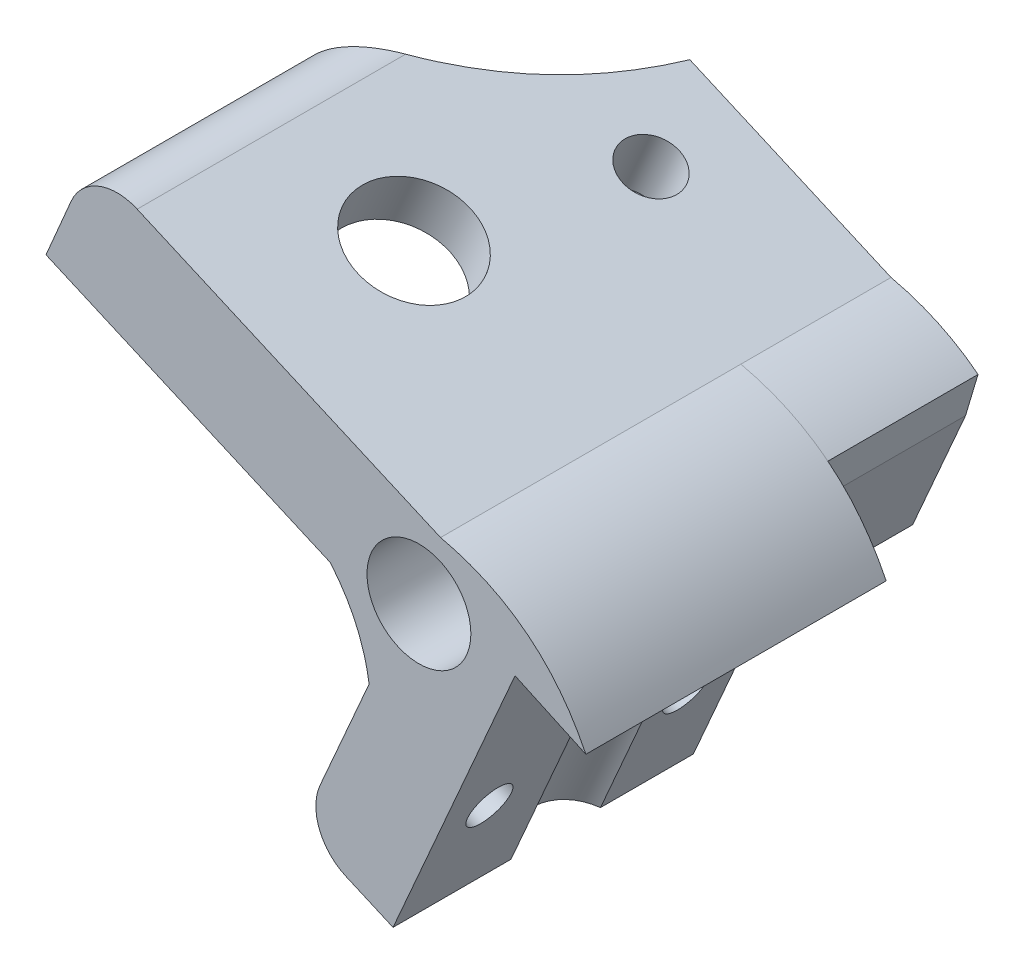
SolidWorks part; units mm, degrees
ref_plane "Front Plane" through (0, 0, 0) normal (0, 0, 1) x (1, 0, 0)
ref_plane "Top Plane" through (0, 0, 0) normal (0, 1, 0) x (1, 0, 0)
ref_plane "Right Plane" through (0, 0, 0) normal (1, 0, 0) x (0, 0, -1)
sketch "Sketch1" plane through (0, 0, 0) normal (0, 0, 1) x (1, 0, 0)
  line L0 (13.3416, -3.7426) -> (7.6824, -1.137)
  line L1 (7.6824, -1.137) -> (-2.0679, -23.4268)
  line L2 (-2.0679, -23.4268) -> (-5.8403, -21.7766)
  line L3 (-7.902, -16.5088) -> (-3.9802, -7.5434)
  line L5 (-7.0804, -0.6853) -> (-29.8034, 9.2544)
  line L6 (-29.8034, 9.2544) -> (-27.7989, 13.9602)
  line L7 (-22.5158, 16.0573) -> (1.7288, 5.4519)
  line L9 (-27.8488, 8.6257) -> (-36.2301, -10.5347) construction
  arc A0 (-27.7989, 13.9602) -> (-22.5158, 16.0573) centre (-24.1189, 12.3926) cw
  circle A1 centre (0, 0) radius 4.15
  arc A2 (-5.8403, -21.7766) -> (-7.902, -16.5088) centre (-4.2373, -18.1119) cw
  spline S0 degree 2 poles (1.7288, 5.4519) (9.7478, 3.6314) (13.3416, -3.7426) knots 0 0 0 1 1 1
  spline S1 degree 2 poles (-7.0804, -0.6853) (-4.5319, -3.7156) (-3.9802, -7.5434) knots 0 0 0 1 1 1
  dimension "D1" = 4
  dimension "D2" = 4
extrude "Boss-Extrude1" add sketch "Sketch1" against normal blind 24
sketch "Sketch3" plane through (0, 0, -24) normal (0, 0, -1) x (-1, 0, 0)
  line L0 (-7.6824, -1.137) -> (-8.6793, 2.213)
  line L1 (3.8269, 1.6054) -> (28.6296, 12.01)
  line L2 (3.5107, 2.213) -> (28.3041, 12.7742)
  line L3 (28.3041, 12.7742) -> (27.7989, 13.9602)
  line L4 (3.9802, -7.5434) -> (-3.4569, -10.7967)
  line L5 (2.0679, -23.4268) -> (-7.6824, -1.137) construction
  line L6 (-3.4569, -10.7967) -> (-7.6824, -1.137)
  line L8 (-13.3416, -3.7426) -> (-7.6824, -1.137)
  line L9 (-7.6824, -1.137) -> (2.0679, -23.4268)
  line L10 (2.0679, -23.4268) -> (5.8403, -21.7766)
  line L11 (7.902, -16.5088) -> (3.9802, -7.5434)
  line L13 (7.0804, -0.6853) -> (29.8034, 9.2544)
  line L14 (29.8034, 9.2544) -> (27.7989, 13.9602)
  line L15 (22.5158, 16.0573) -> (-1.7288, 5.4519)
  line L21 (7.0804, -0.6853) -> (29.8034, 9.2544)
  line L22 (29.8034, 9.2544) -> (28.6296, 12.01)
  line L23 (22.5158, 16.0573) -> (-1.7288, 5.4519)
  circle A0 centre (0, 0) radius 4.15 construction
  arc A1 (3.5107, 2.213) -> (3.8269, 1.6054) centre (0, 0) ccw
  arc A2 (5.8403, -21.7766) -> (7.902, -16.5088) centre (4.2373, -18.1119) ccw
  arc A3 (27.7989, 13.9602) -> (22.5158, 16.0573) centre (24.1189, 12.3926) ccw
  arc A5 (27.7989, 13.9602) -> (22.5158, 16.0573) centre (24.1189, 12.3926) ccw
  parabola Q1 (-1.7288, 5.4519) -> (-13.3416, -3.7426) focus (-3.8657, -3.8279) apex (-8.6793, 2.213)
  parabola Q2 (-1.7288, 5.4519) -> (-8.6793, 2.213) focus (-3.8657, -3.8279) apex (-8.6793, 2.213)
  parabola Q4 (3.9802, -7.5434) -> (7.0804, -0.6853) focus (10.9054, -6.8922) apex (4.8017, -4.454)
  parabola Q5 (3.9802, -7.5434) -> (7.0804, -0.6853) focus (10.9054, -6.8922) apex (4.8017, -4.454)
  dimension "D1" = 0
extrude "Boss-Extrude2" add sketch "Sketch3" along normal blind 12
sketch "Sketch4" plane through (-1.3889, -3.175, 0) normal (-0.4008, -0.9162, 0) x (0.9162, -0.4008, 0)
  circle A0 centre (-13.7076, -28.823) radius 2.25
  dimension "D1" = 4.5
extrude "Cut-Extrude1" cut sketch "Sketch4" against normal through all
sketch "Sketch5" plane through (-1.3889, -3.175, 0) normal (-0.4008, -0.9162, 0) x (0.9162, -0.4008, 0)
  line L0 (-27.0638, -36) -> (-0.601, -36) construction
  line L1 (-31.0638, 0) -> (-31.0638, -36) construction
  line L2 (-18.1493, -36) -> (-34.6973, -37.0234)
  line L3 (-34.6973, -37.0234) -> (-31.0638, -18.4223)
  spline S0 degree 2 poles (-18.1493, -36) (-21.3573, -24.6604) (-31.0638, -18.4223) knots 0 0 0 1 1 1
extrude "Cut-Extrude2" cut sketch "Sketch5" against normal through all
sketch "Sketch6" plane through (-1.3889, -3.175, 0) normal (-0.4008, -0.9162, 0) x (0.9162, -0.4008, 0)
  circle A1 centre (-17, -12.9) radius 10.9
  dimension "D1" = 21.8
extrude "Cut-Extrude3" cut sketch "Sketch6" against normal blind 5
sketch "Sketch7" plane through (2.2795, 5.2111, 0) normal (0.4008, 0.9162, 0) x (0.9162, -0.4008, 0)
  circle A1 centre (-17, 12.9) radius 4.5
  dimension "D1" = 9
extrude "Cut-Extrude4" cut sketch "Sketch7" against normal blind 5
sketch "Sketch8" plane through (-8.9338, -20.4234, 0) normal (-0.4008, -0.9162, 0) x (0.9162, -0.4008, 0)
  circle A1 centre (9.5, -13) radius 4.1
  dimension "D1" = 8.2
extrude "Cut-Extrude5" cut sketch "Sketch8" against normal up to surface (24.2122 mm away)
sketch "Sketch10" plane through (-0.5712, 0.2499, 0) normal (-0.9162, 0.4008, 0) x (0, 0, 1)
  line L0 (0, -8.5063) -> (0, -18.2919) construction
  line L1 (-19.8646, -13.3991) -> (-4.1354, -13.3991) construction
  line L2 (-24, -18.2919) -> (0, -18.2919) construction
  circle A0 centre (-4.1354, -13.3991) radius 3.25
  circle A1 centre (-19.8646, -13.3991) radius 3.25
  point P5 (0, -13.3991)
  point P9 (-12, -18.2919)
  point P10 (-12, -13.3991)
  dimension "D1" = 6.5
  dimension "D2" = 6.5
extrude "Cut-Extrude6" cut sketch "Sketch10" against normal blind 4
sketch "Sketch11" plane through (3.0935, -1.3532, 0) normal (-0.9162, 0.4008, 0) x (0, 0, 1)
  circle A2 centre (-4.1354, -13.3991) radius 1.75
  circle A3 centre (-19.8646, -13.3991) radius 1.75
extrude "Cut-Extrude7" cut sketch "Sketch11" against normal blind 14
